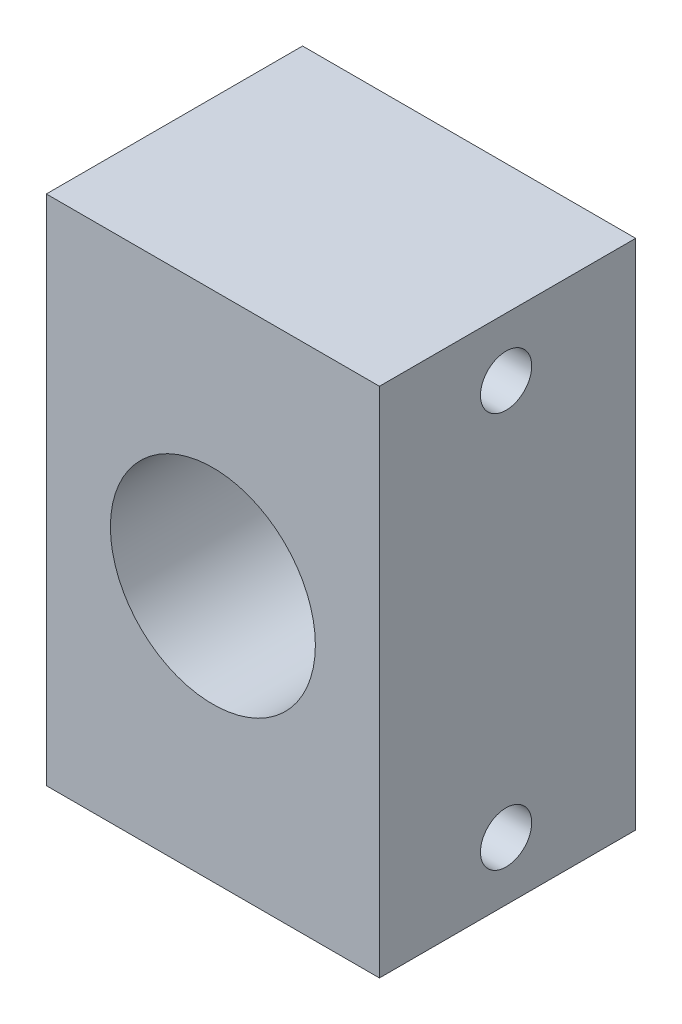
SolidWorks part; units mm, degrees
ref_plane "Front Plane" through (0, 0, 0) normal (0, 0, 1) x (1, 0, 0)
ref_plane "Top Plane" through (0, 0, 0) normal (0, 1, 0) x (1, 0, 0)
ref_plane "Right Plane" through (0, 0, 0) normal (1, 0, 0) x (0, 0, -1)
sketch "Sketch1" plane through (0, 0, 0) normal (0, 0, 1) x (1, 0, 0)
  line L1 (6.5, -10) -> (-6.5, -10)
  line L2 (6.5, -10) -> (6.5, 10)
  line L3 (6.5, 10) -> (-6.5, 10)
  line L4 (-6.5, -10) -> (-6.5, 10)
  line L5 (6.5, -10) -> (-6.5, 10) construction
  line L6 (6.5, 10) -> (-6.5, -10) construction
  circle A0 centre (0, 0) radius 4
  point P0 (0, 0)
  dimension "D1" = 13
  dimension "D2" = 20
extrude "Boss-Extrude1" add sketch "Sketch1" along normal blind 10
sketch "Sketch2" plane through (6.5, 0, 0) normal (1, 0, 0) x (0, 0, -1)
  circle A0 centre (-5.0576, 7.7182) radius 1
extrude "Cut-Extrude1" cut sketch "Sketch2" against normal through all
ref_plane "Plane1" through (0, 0, 0) normal (0, 1, 0) x (1, 0, 0)
mirror "Mirror1" about plane through (0, 0, 0) normal (0, 1, 0) of "Cut-Extrude1"
